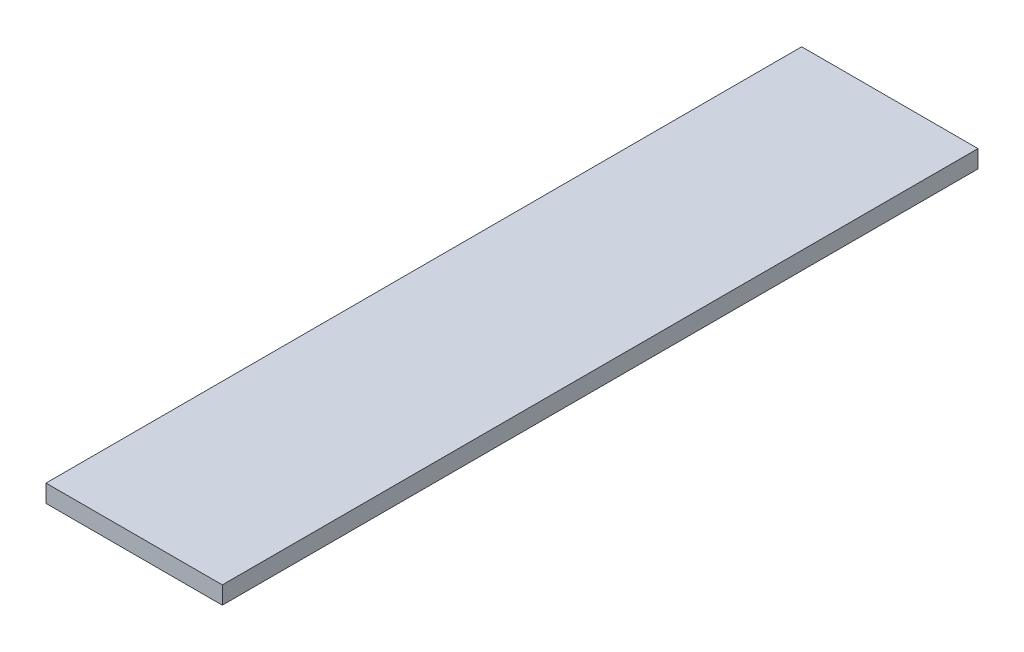
SolidWorks part; units mm, degrees
ref_plane "Front Plane" through (0, 0, 0) normal (0, 0, 1) x (1, 0, 0)
ref_plane "Top Plane" through (0, 0, 0) normal (0, 1, 0) x (1, 0, 0)
ref_plane "Right Plane" through (0, 0, 0) normal (1, 0, 0) x (0, 0, -1)
sketch "Sketch2" plane through (0, 0, 0) normal (0, 0, 1) x (1, 0, 0)
  line L1 (0, 0) -> (70, 0)
  line L2 (0, 0) -> (0, 7)
  line L3 (0, 7) -> (70, 7)
  line L4 (70, 0) -> (70, 7)
  dimension "D1" = 7
  dimension "D2" = 70
extrude "Boss-Extrude1" add sketch "Sketch2" against normal blind 300
